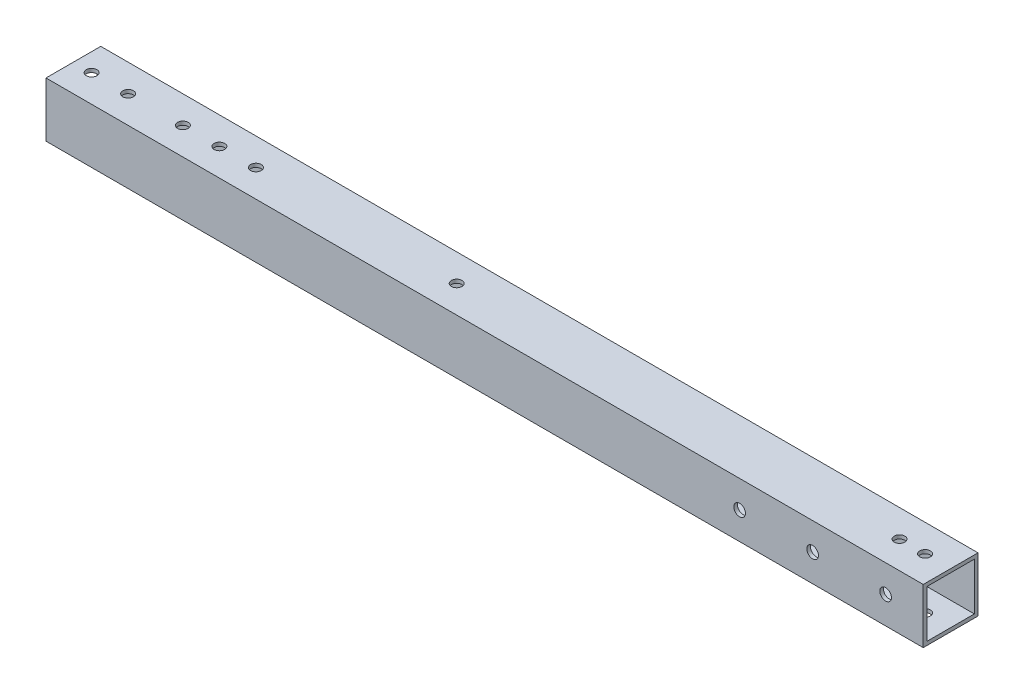
SolidWorks part; units mm, degrees
material "Thornel Mat VMA"
ref_plane "前视基准面" through (0, 0, 0) normal (0, 0, 1) x (1, 0, 0)
ref_plane "上视基准面" through (0, 0, 0) normal (0, 1, 0) x (1, 0, 0)
ref_plane "右视基准面" through (0, 0, 0) normal (1, 0, 0) x (0, 0, -1)
other "Configuration Table"
sketch "草图1" plane through (0, 0, 0) normal (1, 0, 0) x (0, 0, -1)
  line L0 (-6.5, -6.5) -> (-6.5, 6.5)
  line L1 (-7.5, -7.5) -> (7.5, -7.5)
  line L2 (-7.5, -7.5) -> (-7.5, 7.5)
  line L3 (-7.5, 7.5) -> (7.5, 7.5)
  line L4 (7.5, -7.5) -> (7.5, 7.5)
  line L5 (-7.5, -7.5) -> (7.5, 7.5) construction
  line L6 (-7.5, 7.5) -> (7.5, -7.5) construction
  line L7 (-6.5, 6.5) -> (6.5, 6.5)
  line L8 (6.5, -6.5) -> (6.5, 6.5)
  line L9 (-6.5, -6.5) -> (6.5, -6.5)
  point P0 (0, 0)
  dimension "D1" = 15
  dimension "D2" = 15
  dimension "D3" = 1
extrude "凸台-拉伸1" add sketch "草图1" along normal blind 240.3
sketch "草图2" plane through (0, 7.5, 0) normal (0, 1, 0) x (1, 0, 0)
  line L0 (0, 0) -> (139.6107, 0) construction
  circle A0 centre (233.3, 0) radius 1.45 construction
  circle A1 centre (226.3, 0) radius 1.45 construction
  circle A2 centre (14.9985, 0) radius 1.45 construction
  circle A3 centre (4.9985, 0) radius 1.45 construction
  circle A4 centre (233.3, 0) radius 1.45
  circle A5 centre (226.3, 0) radius 1.45
  circle A6 centre (14.9985, 0) radius 1.45
  circle A7 centre (4.9985, 0) radius 1.45
  circle A8 centre (29.9985, 0) radius 1.45
  circle A9 centre (39.9985, 0) radius 1.45
  circle A10 centre (49.9985, 0) radius 1.45
  circle A11 centre (104.9985, 0) radius 1.45
  dimension "D1" = 2.9
  dimension "D2" = 10
  dimension "D3" = 10
  dimension "D4" = 15
  dimension "D5" = 55
  dimension "D6" = 2.9
extrude "切除-拉伸1" cut sketch "草图2" against normal through all
sketch "草图3" plane through (0, 0, 7.5) normal (0, 0, 1) x (1, 0, 0)
  circle A0 centre (229.9985, 0) radius 1.6 construction
  circle A1 centre (189.9985, 0) radius 1.6 construction
  circle A2 centre (209.9985, 0) radius 1.6 construction
  circle A3 centre (229.9985, 0) radius 1.6
  circle A4 centre (189.9985, 0) radius 1.6
  circle A5 centre (209.9985, 0) radius 1.6
extrude "切除-拉伸2" cut sketch "草图3" against normal through all
